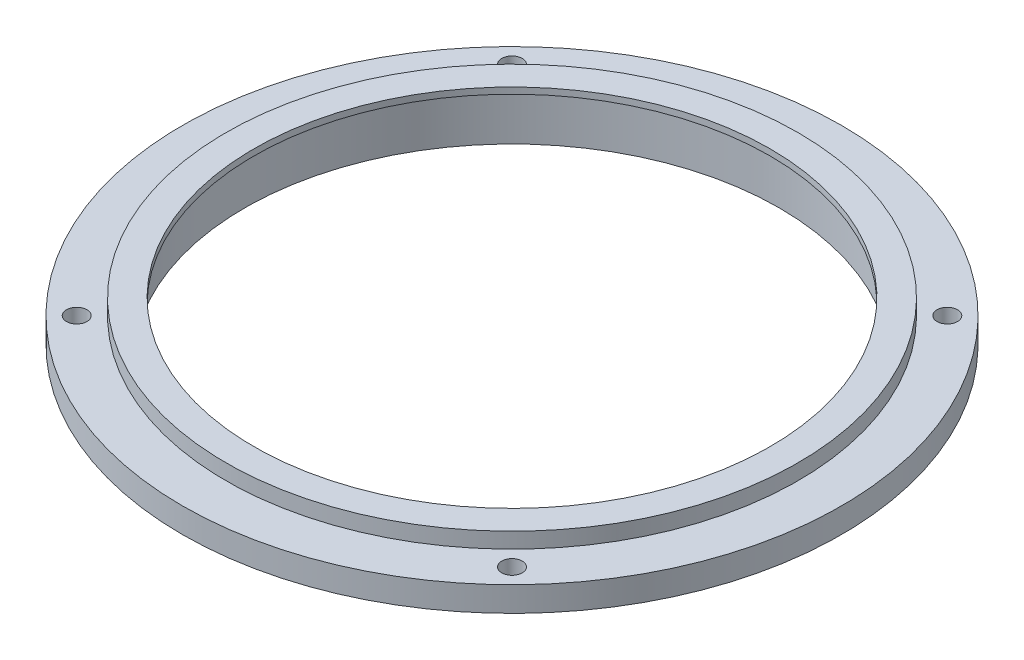
SolidWorks part; units mm, degrees
material "6061 合金"
ref_plane "前视基准面" through (0, 0, 0) normal (0, 0, 1) x (1, 0, 0)
ref_plane "上视基准面" through (0, 0, 0) normal (0, 1, 0) x (1, 0, 0)
ref_plane "右视基准面" through (0, 0, 0) normal (1, 0, 0) x (0, 0, -1)
sketch "草图1" plane through (0, 0, 0) normal (0, 0, 1) x (1, 0, 0)
  line L0 (41.5, 9) -> (46, 9)
  line L1 (43, 8) -> (43, 0)
  line L2 (43, 0) -> (46, 0)
  line L3 (46, 0) -> (46, 2.5)
  line L5 (53, 6.5) -> (53, 2.5)
  line L6 (53, 2.5) -> (46, 2.5)
  line L7 (41.5, 9) -> (41.5, 8)
  line L8 (41.5, 8) -> (43, 8)
  line L9 (0, 0) -> (0, 38.3193) construction
  line L10 (53, 6.5) -> (46, 6.5)
  line L11 (46, 6.5) -> (46, 9)
  dimension "D1" = 86
  dimension "D2" = 83
  dimension "D3" = 8
  dimension "D4" = 3
  dimension "D5" = 7
  dimension "D6" = 5.5
  dimension "D7" = 1
  dimension "D8" = 4
revolve "旋转1" add sketch "草图1" angle 360 about L9
hole_wizard "M4 螺纹孔1" positions "草图2" profile "草图3" tap size "M4" standard "GB" end condition through all
sketch "草图2" plane through (0, 2.5, 0) normal (0, -1, 0) x (-1, 0, 0)
  circle A0 centre (0, 0) radius 49.5 construction
  point P0 (-35.0018, 35.0018)
  point P15 (35.0018, 35.0018)
  point P16 (35.0018, -35.0018)
  point P17 (-35.0018, -35.0018)
  dimension "D1" = 99
  dimension "D2" = 4
sketch "草图3" plane through (35.0018, 2.5, -35.0018) normal (1, 0, 0) x (0, 0, -1)
  line L0 (0, 0) -> (0, 6.5)
  line L1 (0, 6.5) -> (1.65, 6.5)
  line L2 (1.65, 6.5) -> (1.65, 0)
  line L5 (1.65, 0) -> (0, 0)
  line L11 (0, -6.35) -> (0, 107.95) construction
  dimension "通孔螺纹孔钻头直径" = 3.3
  dimension "通孔螺纹孔钻头深度" = 6.5
cosmetic thread "孔螺蚊线1" parameters "D2"=4
cosmetic thread "孔螺蚊线2" parameters "D2"=4
cosmetic thread "孔螺蚊线3" parameters "D2"=4
cosmetic thread "孔螺蚊线4" parameters "D2"=4
